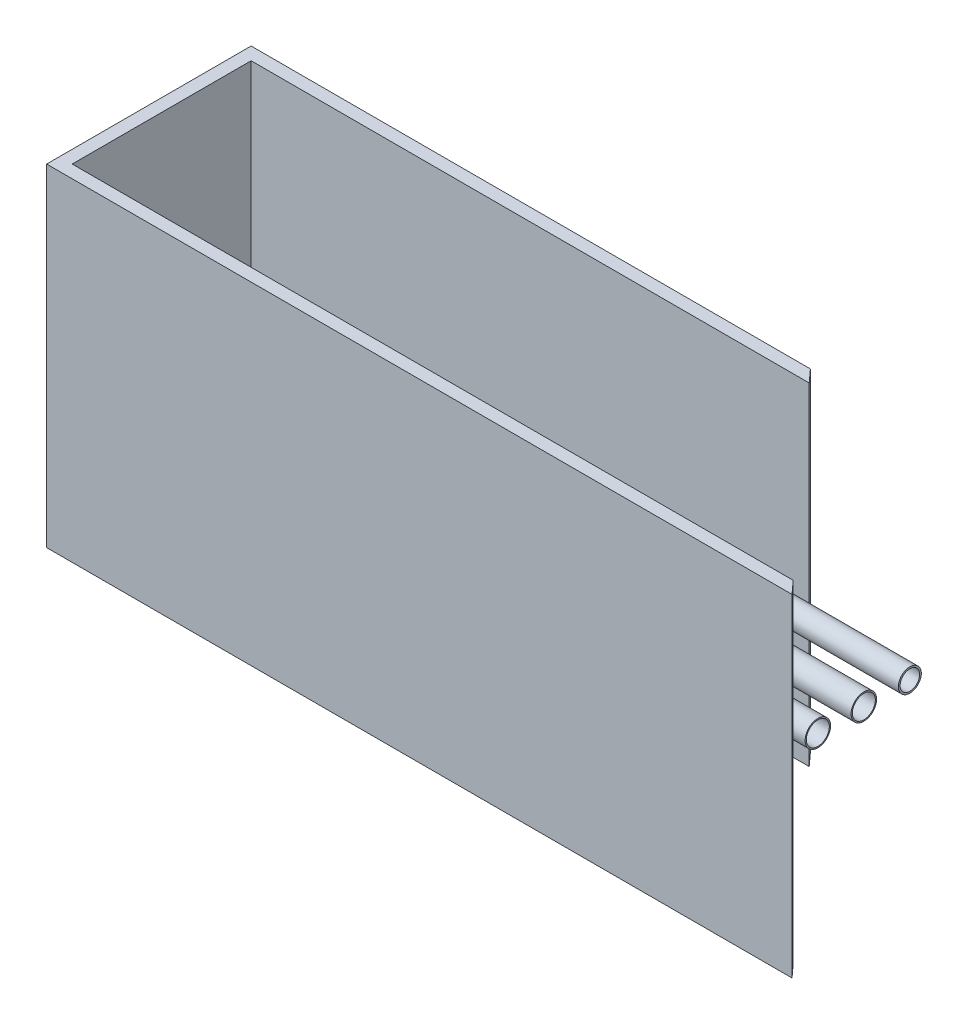
SolidWorks part; units mm, degrees
ref_plane "Alzado" through (0, 0, 0) normal (0, 0, 1) x (1, 0, 0)
ref_plane "Planta" through (0, 0, 0) normal (0, 1, 0) x (1, 0, 0)
ref_plane "Vista lateral" through (0, 0, 0) normal (1, 0, 0) x (0, 0, -1)
sketch "Croquis1" plane through (0, 0, 0) normal (0, 1, 0) x (1, 0, 0)
  line L0 (-1625, 350) -> (1625, 350)
  line L1 (-1675, 400) -> (1675, 400)
  line L2 (-1675, 400) -> (-1675, -400)
  line L3 (-1675, -400) -> (1675, -400)
  line L4 (1675, 400) -> (1675, -400)
  line L5 (-1675, 400) -> (1675, -400) construction
  line L6 (-1675, -400) -> (1675, 400) construction
  line L7 (1625, 350) -> (1625, -350)
  line L8 (-1625, -350) -> (1625, -350)
  line L9 (-1625, 350) -> (-1625, -350)
  point P0 (0, 0)
  dimension "D1" = 3350
  dimension "D2" = 800
  dimension "D3" = 50
extrude "Saliente-Extruir1" add sketch "Croquis1" against normal blind 1200 and the other way blind 100
ref_plane "Plano1" through (0, 0, 0) normal (0, 1, 0) x (1, 0, 0)
sketch "Croquis2" plane through (0, 100, 0) normal (0, 1, 0) x (1, 0, 0)
  line L2 (-1675, -400) -> (1675, -400) construction
  line L3 (1241.5904, -400) -> (513.3475, 400)
  line L4 (1675, 400) -> (-1675, 400) construction
  line L5 (1309.0294, -474.0841) -> (326.2105, 605.5765) construction
  line L6 (513.3475, 400) -> (1675, 400)
  line L7 (1675, 400) -> (1675, -400)
  line L8 (1675, -400) -> (1241.5904, -400)
extrude "Cortar-Extruir1" cut sketch "Croquis2" against normal blind 1448
sketch "Croquis3" plane through (-1675, 0, 0) normal (-1, 0, 0) x (0, 0, 1)
  line L0 (-400, -1200) -> (-400, -550) construction
  line L1 (-400, 100) -> (-400, -1200) construction
  line L2 (-400, -550) -> (400, -550) construction
  line L3 (400, 100) -> (400, -1200) construction
  circle A0 centre (-190.3176, -550) radius 38.1
  circle A1 centre (-190.3176, -550) radius 44.9276
  circle A2 centre (-10.3176, -550) radius 44.9276
  circle A3 centre (169.6824, -550) radius 44.9276
  circle A4 centre (-10.3176, -550) radius 49.9276
  circle A5 centre (169.6824, -550) radius 49.9276
  point P11 (-190.3176, -550)
  dimension "D1" = 76.2
  dimension "D3" = 5
  dimension "D2" = 3
sketch3d "Croquis3D1"
  line L0 (-1675, -550, 169.6824) -> (1112.3417, -550, 169.6824)
  line L1 (-1675, -550, -400) -> (-1675, -550, 400) construction
  point P7 (0, 0, 0)
sweep "Barrer1" add profiles "Croquis3" path "Croquis3D1"
